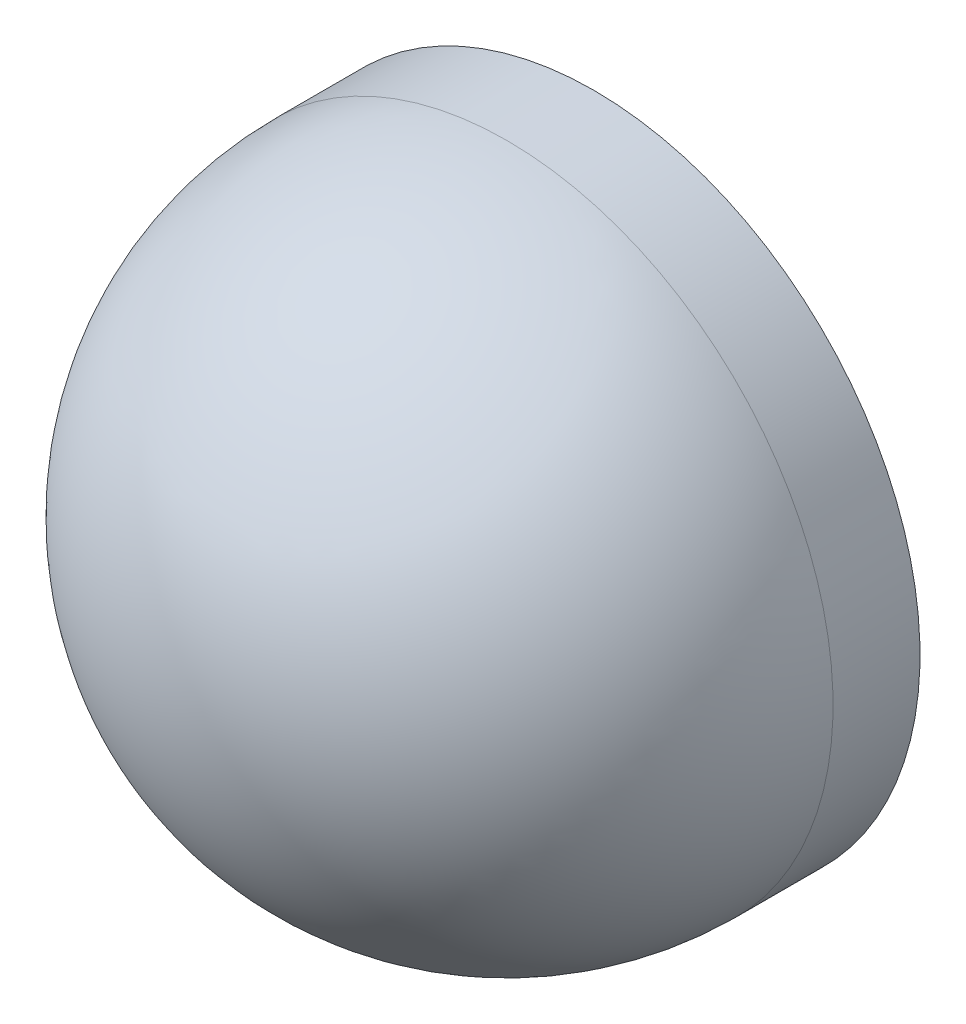
SolidWorks part; units mm, degrees
ref_plane "Ebene vorne" through (0, 0, 0) normal (0, 0, 1) x (1, 0, 0)
ref_plane "Ebene oben" through (0, 0, 0) normal (0, 1, 0) x (1, 0, 0)
ref_plane "Ebene rechts" through (0, 0, 0) normal (1, 0, 0) x (0, 0, -1)
sketch "Skizze2" plane through (0, 0, 0) normal (1, 0, 0) x (0, 0, -1)
  line L0 (-0.8, 0) -> (-3.8, 0) construction
  line L1 (-0.8, 3) -> (0, 3)
  line L2 (0, 3) -> (0, 0)
  line L3 (0, 0) -> (-3.8, 0)
  line L4 (0, 3.3) -> (0, -3.3) construction
  line L5 (1.925, 0) -> (-1.925, 0) construction
  arc A0 (-0.8, 3) -> (-3.8, 0) centre (-0.8, 0) ccw
  dimension "D1" = 3
  dimension "D2" = 0.8
revolve "Rotation2" add sketch "Skizze2" angle 360 about L0
sketch "Skizze3" plane through (0, 0, 0) normal (0, 0, -1) x (-1, 0, 0)
  line L1 (1.65, 1.45) -> (-1.65, 1.45)
  line L2 (1.65, 1.45) -> (1.65, -1.45)
  line L3 (1.65, -1.45) -> (-1.65, -1.45)
  line L4 (-1.65, 1.45) -> (-1.65, -1.45)
  line L5 (1.65, 1.45) -> (-1.65, -1.45) construction
  line L6 (1.65, -1.45) -> (-1.65, 1.45) construction
  point P0 (0, 0)
  dimension "D1" = 2.9
  dimension "D2" = 3.3
extrude "Schnitt-Linear austragen1" cut sketch "Skizze3" against normal blind 2.5
